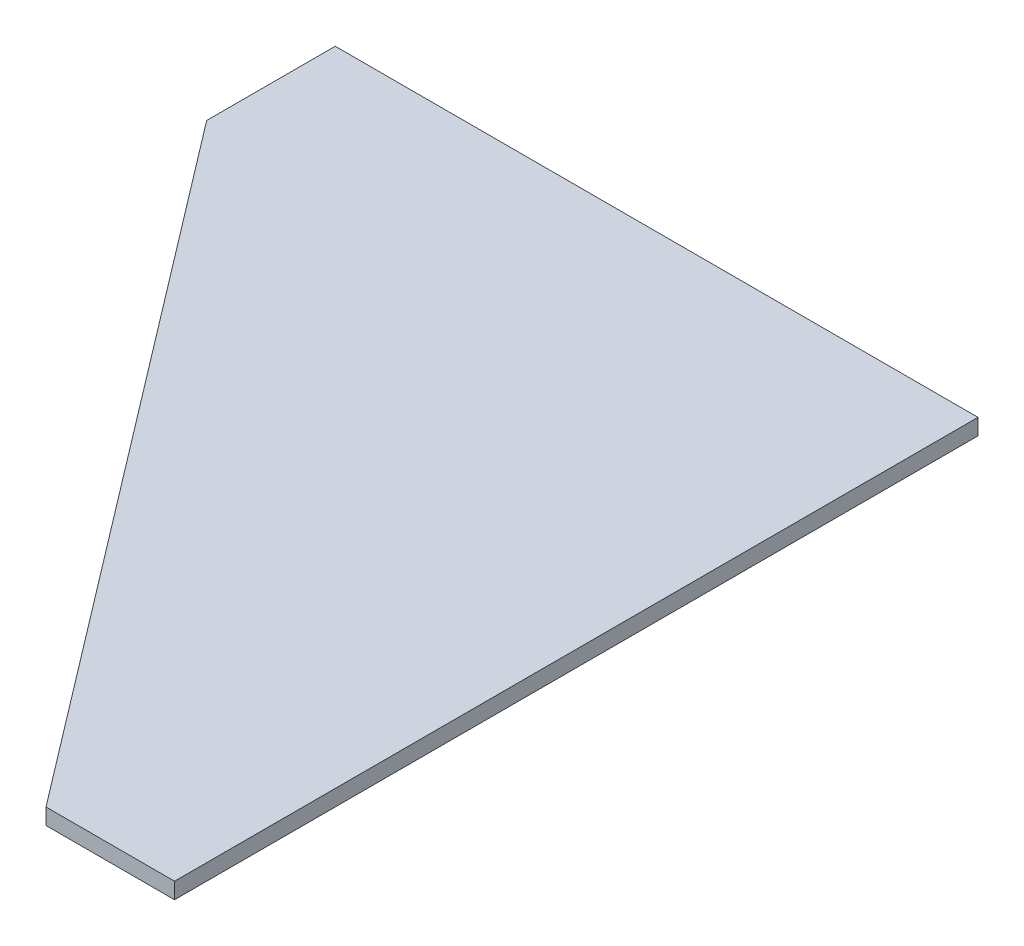
SolidWorks part; units mm, degrees
ref_plane "Front Plane" through (0, 0, 0) normal (0, 0, 1) x (1, 0, 0)
ref_plane "Top Plane" through (0, 0, 0) normal (0, 1, 0) x (1, 0, 0)
ref_plane "Right Plane" through (0, 0, 0) normal (1, 0, 0) x (0, 0, -1)
sketch "Sketch1" plane through (0, 0, 0) normal (0, 1, 0) x (1, 0, 0)
  line L0 (-12.7, 79.375) -> (-114.3, 79.375)
  line L1 (-12.7, 79.375) -> (12.7, 79.375)
  line L2 (-12.7, 79.375) -> (-12.7, -79.375)
  line L3 (-12.7, -79.375) -> (12.7, -79.375)
  line L4 (12.7, 79.375) -> (12.7, -79.375)
  line L5 (-12.7, 79.375) -> (12.7, -79.375) construction
  line L6 (-12.7, -79.375) -> (12.7, 79.375) construction
  line L7 (-114.3, 79.375) -> (-114.3, 53.975)
  line L8 (-114.3, 53.975) -> (-12.7, 53.975)
  line L9 (-114.3, 53.975) -> (-12.7, -79.375)
  point P0 (0, 0)
  dimension "D1" = 25.4
  dimension "D2" = 158.75
  dimension "D3" = 101.6
  dimension "D4" = 25.4
extrude "Boss-Extrude1" add sketch "Sketch1" along normal blind 3.175 contours L7 L8 L2 L0 | L8 L9 L2 | L4 L1 L2 L3
sketch "Sketch3" plane through (0, 3.175, 0) normal (0, 1, 0) x (1, 0, 0)
  line L0 (-114.3, 115.855) -> (-114.3, -15.6078) construction
  line L1 (-111.5798, -20.8181) -> (23.3362, -114.808) construction
  line L2 (-114.3, 115.855) -> (-114.3, -15.6078)
  line L3 (-111.5798, -20.8181) -> (23.3362, -114.808)
  line L4 (-127.762, 77.343) -> (-127.762, 65.913)
  line L5 (-125.7106, 60.9159) -> (-98.9065, 33.771)
  line L6 (-114.3, 53.975) -> (-12.7, -79.375) construction
  line L7 (-120.0168, 84.4268) -> (-63.5, 79.375)
  line L8 (12.7, 79.375) -> (-114.3, 79.375) construction
  line L9 (-19.3358, -105.5129) -> (-19.3358, -123.2929)
  line L10 (-16.491, -128.9825) -> (3.829, -144.2225)
  line L11 (15.2082, -120.7529) -> (15.2082, -138.5329)
  line L12 (12.3634, -115.0633) -> (-7.9566, -99.8233)
  line L13 (-19.3357, -70.6656) -> (-19.3358, -105.5129)
  line L14 (15.2082, 79.375) -> (15.2082, -120.7529)
  line L15 (15.2082, 79.375) -> (12.7, 79.375)
  line L18 (-114.3, 53.975) -> (-12.7, -79.375)
  line L19 (-12.7, -79.375) -> (12.7, -79.375)
  line L20 (12.7, -79.375) -> (12.7, 79.375)
  line L21 (12.7, 79.375) -> (-114.3, 79.375)
  line L22 (-114.3, 79.375) -> (-114.3, 53.975)
  line L23 (-114.3, 53.975) -> (-12.7, -79.375)
  line L24 (-12.7, -79.375) -> (12.7, -79.375)
  line L25 (12.7, -79.375) -> (12.7, 79.375)
  line L26 (12.7, 79.375) -> (-114.3, 79.375)
  line L27 (-114.3, 79.375) -> (-114.3, 53.975)
  circle A0 centre (8.0962, -138.5329) radius 2.032 construction
  circle A1 centre (8.0962, -120.7529) radius 2.032 construction
  circle A2 centre (-12.2238, -123.2929) radius 2.032 construction
  circle A3 centre (-12.2238, -105.5129) radius 2.032 construction
  circle A4 centre (-120.65, 65.913) radius 2.032 construction
  circle A5 centre (-120.65, 77.343) radius 2.032 construction
  circle A6 centre (8.0962, -138.5329) radius 2.032
  circle A7 centre (8.0962, -120.7529) radius 2.032
  circle A8 centre (-12.2238, -123.2929) radius 2.032
  circle A9 centre (-12.2238, -105.5129) radius 2.032
  circle A10 centre (-120.65, 65.913) radius 2.032
  circle A11 centre (-120.65, 77.343) radius 2.032
  arc A12 (-114.3, -15.6078) -> (-111.5798, -20.8181) centre (-107.95, -15.6078) ccw construction
  arc A13 (-114.3, -15.6078) -> (-111.5798, -20.8181) centre (-107.95, -15.6078) ccw
  circle A14 centre (-120.65, 65.913) radius 7.112
  circle A15 centre (-120.65, 77.343) radius 7.112
  circle A16 centre (-12.2238, -105.5129) radius 7.112
  circle A17 centre (-12.2238, -123.2929) radius 7.112
  circle A18 centre (8.0962, -120.7529) radius 7.112
  circle A19 centre (8.0962, -138.5329) radius 7.112
  point P38 (-125.1906, 60.4391)
  dimension "D2" = 0
  dimension "D3" = 25.4
  dimension "D4" = 50.8
  dimension "D1" = 5.08
